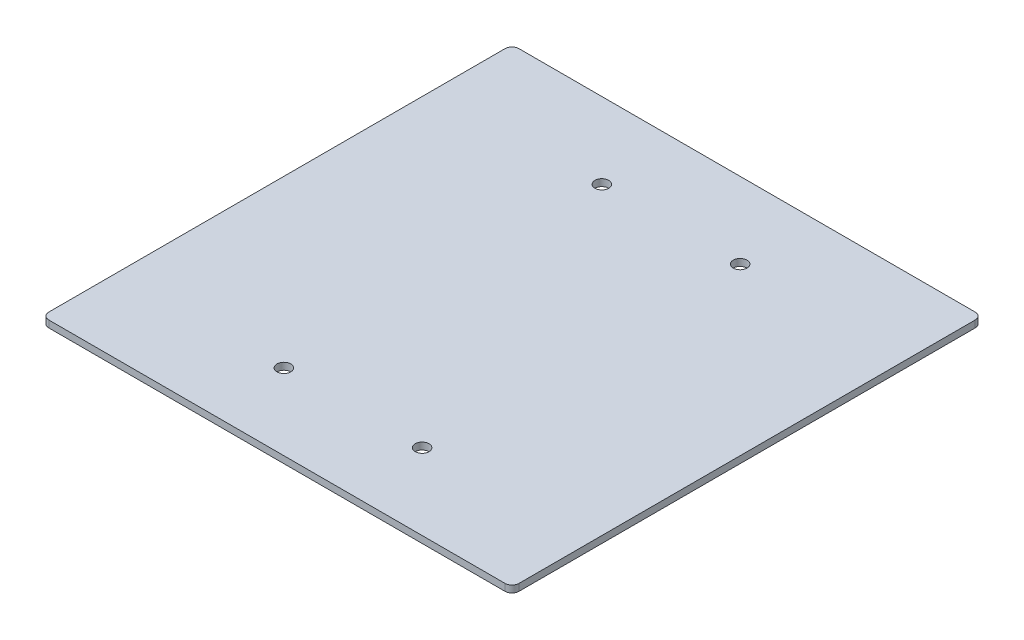
SolidWorks part; units mm, degrees
ref_plane "Front Plane" through (0, 0, 0) normal (0, 0, 1) x (1, 0, 0)
ref_plane "Top Plane" through (0, 0, 0) normal (0, 1, 0) x (1, 0, 0)
ref_plane "Right Plane" through (0, 0, 0) normal (1, 0, 0) x (0, 0, -1)
sketch "Sketch2" plane through (0, 0, 0) normal (0, 1, 0) x (1, 0, 0)
  line L1 (0, 0) -> (215.9, 0)
  line L2 (0, 0) -> (0, 215.9)
  line L3 (0, 215.9) -> (215.9, 215.9)
  line L4 (215.9, 0) -> (215.9, 215.9)
  dimension "D1" = 215.9
  dimension "D2" = 215.9
extrude "Boss-Extrude1" add sketch "Sketch2" along normal blind 3.175
fillet "Fillet1" radius 3.175 4 edges at (215.9, 1.5875, -215.9) (0, 1.5875, -215.9) (0, 1.5875, 0) (215.9, 1.5875, 0)
sketch "Sketch4" plane through (0, 3.175, 0) normal (0, 1, 0) x (1, 0, 0)
  line L0 (76.2, 215.9) -> (76.2, 0) construction
  line L1 (212.725, 215.9) -> (3.175, 215.9) construction
  line L2 (3.175, 0) -> (212.725, 0) construction
  line L3 (0, 34.925) -> (215.9, 34.925) construction
  line L4 (139.7, 0) -> (139.7, 215.9) construction
  line L5 (0, 212.725) -> (0, 3.175) construction
  line L6 (215.9, 3.175) -> (215.9, 212.725) construction
  line L7 (215.9, 34.925) -> (215.9, 180.975)
  line L8 (215.9, 180.975) -> (0, 180.975) construction
  circle A0 centre (76.2, 180.975) radius 3.175
  circle A1 centre (139.7, 180.975) radius 3.175
  circle A2 centre (139.7, 34.925) radius 3.175
  circle A3 centre (76.2, 34.925) radius 3.175
  dimension "D1" = 76.2
  dimension "D2" = 139.7
  dimension "D3" = 180.975
  dimension "D4" = 34.925
extrude "Cut-Extrude1" cut sketch "Sketch4" against normal through all contours A0 | A1 | A2 | A3
